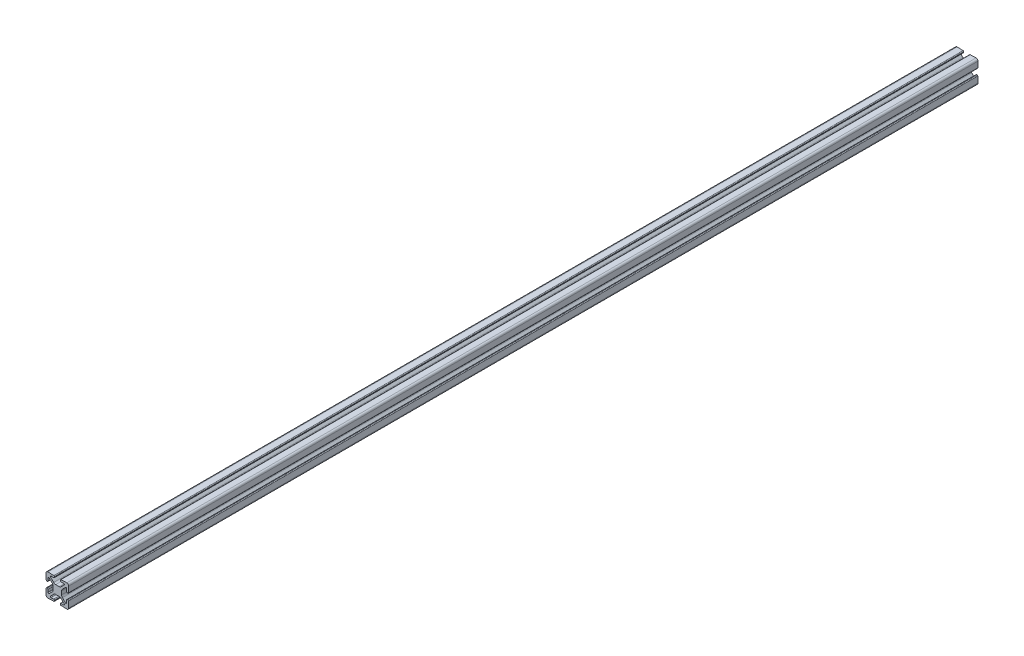
SolidWorks part; units mm, degrees
ref_plane "Front Plane" through (0, 0, 0) normal (0, 0, 1) x (1, 0, 0)
ref_plane "Top Plane" through (0, 0, 0) normal (0, 1, 0) x (1, 0, 0)
ref_plane "Right Plane" through (0, 0, 0) normal (1, 0, 0) x (0, 0, -1)
sketch "Sketch1" plane through (0, 0, 0) normal (0, 0, 1) x (1, 0, 0)
  line L0 (0, 0) -> (0, 12.7) construction
  line L1 (0, 0) -> (12.7, 0) construction
  line L2 (0, 0) -> (-12.7, 12.7) construction
  line L3 (-10.5971, 12.6988) -> (-3.9739, 12.4675)
  line L4 (-12.7, 12.7) -> (0, 12.7) construction
  line L6 (-4.0475, 10.3606) -> (-7.0332, 10.4648)
  line L10 (0, 4.7625) -> (-1.8848, 4.7625)
  line L11 (-4.1299, 5.6924) -> (-7.5996, 9.1622)
  line L24 (0, 0) -> (-12.7, 0) construction
  line L25 (-12.7, 0) -> (0, 0) construction
  line L26 (0, 0) -> (0, -12.7) construction
  line L27 (-12.7, -12.7) -> (-12.7, 12.7) construction
  line L28 (0, 12.7) -> (12.7, 12.7) construction
  line L29 (-3.239, 11.6793) -> (-3.2594, 11.0955)
  line L30 (-12.7, -12.7) -> (12.7, -12.7) construction
  arc A0 (-12.1048, 12.1048) -> (-10.5971, 12.6988) centre (-10.668, 10.668) cw
  arc A6 (-1.8848, 4.7625) -> (-4.1299, 5.6924) centre (-1.8848, 7.9375) cw
  circle A16 centre (0, 0) radius 2.54
  arc A18 (-7.5996, 9.1622) -> (-7.0332, 10.4648) centre (-7.0599, 9.702) cw
  circle A19 centre (-2.3794, 2.3794) radius 0.635 construction
  arc A20 (-4.0475, 10.3606) -> (-3.2594, 11.0955) centre (-4.0209, 11.1221) ccw
  arc A21 (-3.9739, 12.4675) -> (-3.239, 11.6793) centre (-4.0005, 11.7059) cw
  point P15 (0, 0)
  point P42 (-3.1999, 4.7625)
  point P80 (-12.7, 0)
  point P85 (0, -12.7)
  point P88 (0, -12.7)
  dimension "D11" = 2.032
  dimension "D15" = 3.175
  dimension "Center Hole Diameter" = 5.08
  dimension "D6" = 1.27
  dimension "D4" = 0.7633
  dimension "D8" = 0.762
  dimension "D12" = 0.762
  dimension "D1" = 45
  dimension "D2" = 2
  dimension "Rail Width" = 25.4
  dimension "D10" = 2.2098
  dimension "T-Slot Depth" = 7.9375
  dimension "D9" = 2.1082
  dimension "Rail Height" = 25.4
  dimension "D23" = 9.525
  dimension "D5" = 15.6464
  dimension "D3" = 4
  dimension "D7" = 5.7028
  dimension "T-Slot Width" = 6.477
sketch "Sketch2" plane through (0, 0, 0) normal (1, 0, 0) x (0, 0, -1)
  line L0 (-457.2, 0) -> (457.2, 0)
  line L2 (0, 0) -> (0, 12.7) construction
  line L3 (0, 0) -> (0, 12.7) construction
  point P0 (-419.1, 0)
  point P3 (0, 0)
  point P7 (419.1, 0)
  dimension "D1" = 38.1
  dimension "Length" = 914.4
sketch "Sketch3" plane through (0, 0, 0) normal (0, 0, 1) x (1, 0, 0)
  line L2 (0, 4.7625) -> (-1.8848, 4.7625) construction
  line L5 (-4.1299, 5.6924) -> (-7.5996, 9.1622) construction
  line L6 (-4.0475, 10.3606) -> (-7.0332, 10.4648) construction
  line L7 (-3.239, 11.6793) -> (-3.2594, 11.0955) construction
  line L67 (-10.5971, 12.6988) -> (-3.9739, 12.4675) construction
  line L68 (0, 4.7625) -> (-1.8848, 4.7625)
  line L69 (-4.1299, 5.6924) -> (-7.5996, 9.1622)
  line L70 (-4.0475, 10.3606) -> (-7.0332, 10.4648)
  line L71 (-3.239, 11.6793) -> (-3.2594, 11.0955)
  line L72 (-10.5971, 12.6988) -> (-3.9739, 12.4675)
  line L73 (0, 0) -> (-12.7, 12.7) construction
  line L74 (0, 0) -> (-12.7, 12.7) construction
  line L75 (-12.6988, 10.5971) -> (-12.4675, 3.9739)
  line L76 (-11.6793, 3.239) -> (-11.0955, 3.2594)
  line L77 (-10.3606, 4.0475) -> (-10.4648, 7.0332)
  line L78 (-5.6924, 4.1299) -> (-9.1622, 7.5996)
  line L79 (-4.7625, 0) -> (-4.7625, 1.8848)
  line L80 (-4.7625, 0) -> (-2.54, 0)
  line L82 (0, 4.7625) -> (0, 2.54)
  arc A3 (-4.1299, 5.6924) -> (-1.8848, 4.7625) centre (-1.8848, 7.9375) ccw construction
  circle A10 centre (0, 0) radius 2.54
  arc A56 (0, 2.54) -> (-2.54, 0) centre (0, 0) ccw
  arc A57 (-7.0332, 10.4648) -> (-7.5996, 9.1622) centre (-7.0599, 9.702) ccw construction
  arc A58 (-4.0475, 10.3606) -> (-3.2594, 11.0955) centre (-4.0209, 11.1221) ccw construction
  arc A59 (-3.239, 11.6793) -> (-3.9739, 12.4675) centre (-4.0005, 11.7059) ccw construction
  arc A60 (-10.5971, 12.6988) -> (-12.1048, 12.1048) centre (-10.668, 10.668) ccw construction
  arc A61 (-4.1299, 5.6924) -> (-1.8848, 4.7625) centre (-1.8848, 7.9375) ccw
  arc A62 (-7.0332, 10.4648) -> (-7.5996, 9.1622) centre (-7.0599, 9.702) ccw
  arc A63 (-4.0475, 10.3606) -> (-3.2594, 11.0955) centre (-4.0209, 11.1221) ccw
  arc A64 (-3.239, 11.6793) -> (-3.9739, 12.4675) centre (-4.0005, 11.7059) ccw
  arc A65 (-10.5971, 12.6988) -> (-12.6988, 10.5971) centre (-10.668, 10.668) ccw
  arc A67 (-11.6793, 3.239) -> (-12.4675, 3.9739) centre (-11.7059, 4.0005) cw
  arc A68 (-10.3606, 4.0475) -> (-11.0955, 3.2594) centre (-11.1221, 4.0209) cw
  arc A69 (-10.4648, 7.0332) -> (-9.1622, 7.5996) centre (-9.702, 7.0599) cw
  arc A70 (-5.6924, 4.1299) -> (-4.7625, 1.8848) centre (-7.9375, 1.8848) cw
  dimension "D1" = 0
extrude "Boss-Extrude1" add sketch "Sketch3" along normal mid plane 914.4
pattern_circular "CirPattern1" count 4 over 360 about axis through (0, 0, 0) along (0, 0, 1) of "Boss-Extrude1"
ref_plane "Contact Plane 1" through (0, 12.7, 0) normal (0, 1, 0) x (1, 0, 0)
ref_plane "Contact Plane 2" through (12.7, 0, 0) normal (1, 0, 0) x (0, 0, -1)
ref_plane "Contact Plane 3" through (0, -12.7, 0) normal (0, -1, 0) x (-1, 0, 0)
ref_plane "Contact Plane 4" through (-12.7, 0, 0) normal (-1, 0, 0) x (0, 0, 1)
sketch "Sketch4" plane through (0, 0, 457.2) normal (0, 0, 1) x (1, 0, 0)
  line L36 (1.8848, 4.7625) -> (-1.8848, 4.7625)
  line L37 (-4.1299, 5.6924) -> (-7.5996, 9.1622)
  line L38 (-7.0332, 10.4648) -> (-4.0475, 10.3606)
  line L39 (-3.2594, 11.0955) -> (-3.239, 11.6793)
  line L40 (-3.9739, 12.4675) -> (-10.5971, 12.6988)
  line L41 (-12.6988, 10.5971) -> (-12.4675, 3.9739)
  line L42 (-11.6793, 3.239) -> (-11.0955, 3.2594)
  line L43 (-10.3606, 4.0475) -> (-10.4648, 7.0332)
  line L44 (-9.1622, 7.5996) -> (-5.6924, 4.1299)
  line L45 (-4.7625, 1.8848) -> (-4.7625, -1.8848)
  line L46 (-5.6924, -4.1299) -> (-9.1622, -7.5996)
  line L47 (-10.4648, -7.0332) -> (-10.3606, -4.0475)
  line L48 (-11.0955, -3.2594) -> (-11.6793, -3.239)
  line L49 (-12.4675, -3.9739) -> (-12.6988, -10.5971)
  line L50 (-10.5971, -12.6988) -> (-3.9739, -12.4675)
  line L51 (-3.239, -11.6793) -> (-3.2594, -11.0955)
  line L52 (-4.0475, -10.3606) -> (-7.0332, -10.4648)
  line L53 (-7.5996, -9.1622) -> (-4.1299, -5.6924)
  line L54 (-1.8848, -4.7625) -> (1.8848, -4.7625)
  line L55 (4.1299, -5.6924) -> (7.5996, -9.1622)
  line L56 (7.0332, -10.4648) -> (4.0475, -10.3606)
  line L57 (3.2594, -11.0955) -> (3.239, -11.6793)
  line L58 (3.9739, -12.4675) -> (10.5971, -12.6988)
  line L59 (12.6988, -10.5971) -> (12.4675, -3.9739)
  line L60 (11.6793, -3.239) -> (11.0955, -3.2594)
  line L61 (10.3606, -4.0475) -> (10.4648, -7.0332)
  line L62 (9.1622, -7.5996) -> (5.6924, -4.1299)
  line L63 (4.7625, -1.8848) -> (4.7625, 1.8848)
  line L64 (5.6924, 4.1299) -> (9.1622, 7.5996)
  line L65 (10.4648, 7.0332) -> (10.3606, 4.0475)
  line L66 (11.0955, 3.2594) -> (11.6793, 3.239)
  line L67 (12.4675, 3.9739) -> (12.6988, 10.5971)
  line L68 (10.5971, 12.6988) -> (3.9739, 12.4675)
  line L69 (3.239, 11.6793) -> (3.2594, 11.0955)
  line L70 (4.0475, 10.3606) -> (7.0332, 10.4648)
  line L71 (7.5996, 9.1622) -> (4.1299, 5.6924)
  line L72 (1.8848, 4.7625) -> (-1.8848, 4.7625)
  line L73 (-4.1299, 5.6924) -> (-7.5996, 9.1622)
  line L74 (-7.0332, 10.4648) -> (-4.0475, 10.3606)
  line L75 (-3.2594, 11.0955) -> (-3.239, 11.6793)
  line L76 (-3.9739, 12.4675) -> (-10.5971, 12.6988)
  line L77 (-12.6988, 10.5971) -> (-12.4675, 3.9739)
  line L78 (-11.6793, 3.239) -> (-11.0955, 3.2594)
  line L79 (-10.3606, 4.0475) -> (-10.4648, 7.0332)
  line L80 (-9.1622, 7.5996) -> (-5.6924, 4.1299)
  line L81 (-4.7625, 1.8848) -> (-4.7625, -1.8848)
  line L82 (-5.6924, -4.1299) -> (-9.1622, -7.5996)
  line L83 (-10.4648, -7.0332) -> (-10.3606, -4.0475)
  line L84 (-11.0955, -3.2594) -> (-11.6793, -3.239)
  line L85 (-12.4675, -3.9739) -> (-12.6988, -10.5971)
  line L86 (-10.5971, -12.6988) -> (-3.9739, -12.4675)
  line L87 (-3.239, -11.6793) -> (-3.2594, -11.0955)
  line L88 (-4.0475, -10.3606) -> (-7.0332, -10.4648)
  line L89 (-7.5996, -9.1622) -> (-4.1299, -5.6924)
  line L90 (-1.8848, -4.7625) -> (1.8848, -4.7625)
  line L91 (4.1299, -5.6924) -> (7.5996, -9.1622)
  line L92 (7.0332, -10.4648) -> (4.0475, -10.3606)
  line L93 (3.2594, -11.0955) -> (3.239, -11.6793)
  line L94 (3.9739, -12.4675) -> (10.5971, -12.6988)
  line L95 (12.6988, -10.5971) -> (12.4675, -3.9739)
  line L96 (11.6793, -3.239) -> (11.0955, -3.2594)
  line L97 (10.3606, -4.0475) -> (10.4648, -7.0332)
  line L98 (9.1622, -7.5996) -> (5.6924, -4.1299)
  line L99 (4.7625, -1.8848) -> (4.7625, 1.8848)
  line L100 (5.6924, 4.1299) -> (9.1622, 7.5996)
  line L101 (10.4648, 7.0332) -> (10.3606, 4.0475)
  line L102 (11.0955, 3.2594) -> (11.6793, 3.239)
  line L103 (12.4675, 3.9739) -> (12.6988, 10.5971)
  line L104 (10.5971, 12.6988) -> (3.9739, 12.4675)
  line L105 (3.239, 11.6793) -> (3.2594, 11.0955)
  line L106 (4.0475, 10.3606) -> (7.0332, 10.4648)
  line L107 (7.5996, 9.1622) -> (4.1299, 5.6924)
  arc A36 (1.8848, 4.7625) -> (4.1299, 5.6924) centre (1.8848, 7.9375) ccw
  arc A37 (-4.1299, 5.6924) -> (-1.8848, 4.7625) centre (-1.8848, 7.9375) ccw
  arc A38 (-7.0332, 10.4648) -> (-7.5996, 9.1622) centre (-7.0599, 9.702) ccw
  arc A39 (-4.0475, 10.3606) -> (-3.2594, 11.0955) centre (-4.0209, 11.1221) ccw
  arc A40 (-3.239, 11.6793) -> (-3.9739, 12.4675) centre (-4.0005, 11.7059) ccw
  arc A41 (-10.5971, 12.6988) -> (-12.6988, 10.5971) centre (-10.668, 10.668) ccw
  arc A42 (-12.4675, 3.9739) -> (-11.6793, 3.239) centre (-11.7059, 4.0005) ccw
  arc A43 (-11.0955, 3.2594) -> (-10.3606, 4.0475) centre (-11.1221, 4.0209) ccw
  arc A44 (-9.1622, 7.5996) -> (-10.4648, 7.0332) centre (-9.702, 7.0599) ccw
  arc A45 (-4.7625, 1.8848) -> (-5.6924, 4.1299) centre (-7.9375, 1.8848) ccw
  arc A46 (-5.6924, -4.1299) -> (-4.7625, -1.8848) centre (-7.9375, -1.8848) ccw
  arc A47 (-10.4648, -7.0332) -> (-9.1622, -7.5996) centre (-9.702, -7.0599) ccw
  arc A48 (-10.3606, -4.0475) -> (-11.0955, -3.2594) centre (-11.1221, -4.0209) ccw
  arc A49 (-11.6793, -3.239) -> (-12.4675, -3.9739) centre (-11.7059, -4.0005) ccw
  arc A50 (-12.6988, -10.5971) -> (-10.5971, -12.6988) centre (-10.668, -10.668) ccw
  arc A51 (-3.9739, -12.4675) -> (-3.239, -11.6793) centre (-4.0005, -11.7059) ccw
  arc A52 (-3.2594, -11.0955) -> (-4.0475, -10.3606) centre (-4.0209, -11.1221) ccw
  arc A53 (-7.5996, -9.1622) -> (-7.0332, -10.4648) centre (-7.0599, -9.702) ccw
  arc A54 (-1.8848, -4.7625) -> (-4.1299, -5.6924) centre (-1.8848, -7.9375) ccw
  arc A55 (4.1299, -5.6924) -> (1.8848, -4.7625) centre (1.8848, -7.9375) ccw
  arc A56 (7.0332, -10.4648) -> (7.5996, -9.1622) centre (7.0599, -9.702) ccw
  arc A57 (4.0475, -10.3606) -> (3.2594, -11.0955) centre (4.0209, -11.1221) ccw
  arc A58 (3.239, -11.6793) -> (3.9739, -12.4675) centre (4.0005, -11.7059) ccw
  arc A59 (10.5971, -12.6988) -> (12.6988, -10.5971) centre (10.668, -10.668) ccw
  arc A60 (12.4675, -3.9739) -> (11.6793, -3.239) centre (11.7059, -4.0005) ccw
  arc A61 (11.0955, -3.2594) -> (10.3606, -4.0475) centre (11.1221, -4.0209) ccw
  arc A62 (9.1622, -7.5996) -> (10.4648, -7.0332) centre (9.702, -7.0599) ccw
  arc A63 (4.7625, -1.8848) -> (5.6924, -4.1299) centre (7.9375, -1.8848) ccw
  arc A64 (5.6924, 4.1299) -> (4.7625, 1.8848) centre (7.9375, 1.8848) ccw
  arc A65 (10.4648, 7.0332) -> (9.1622, 7.5996) centre (9.702, 7.0599) ccw
  arc A66 (10.3606, 4.0475) -> (11.0955, 3.2594) centre (11.1221, 4.0209) ccw
  arc A67 (11.6793, 3.239) -> (12.4675, 3.9739) centre (11.7059, 4.0005) ccw
  arc A68 (12.6988, 10.5971) -> (10.5971, 12.6988) centre (10.668, 10.668) ccw
  arc A69 (3.9739, 12.4675) -> (3.239, 11.6793) centre (4.0005, 11.7059) ccw
  arc A70 (3.2594, 11.0955) -> (4.0475, 10.3606) centre (4.0209, 11.1221) ccw
  arc A71 (7.5996, 9.1622) -> (7.0332, 10.4648) centre (7.0599, 9.702) ccw
  arc A72 (1.8848, 4.7625) -> (4.1299, 5.6924) centre (1.8848, 7.9375) ccw
  arc A73 (-4.1299, 5.6924) -> (-1.8848, 4.7625) centre (-1.8848, 7.9375) ccw
  arc A74 (-7.0332, 10.4648) -> (-7.5996, 9.1622) centre (-7.0599, 9.702) ccw
  arc A75 (-4.0475, 10.3606) -> (-3.2594, 11.0955) centre (-4.0209, 11.1221) ccw
  arc A76 (-3.239, 11.6793) -> (-3.9739, 12.4675) centre (-4.0005, 11.7059) ccw
  arc A77 (-10.5971, 12.6988) -> (-12.6988, 10.5971) centre (-10.668, 10.668) ccw
  arc A78 (-12.4675, 3.9739) -> (-11.6793, 3.239) centre (-11.7059, 4.0005) ccw
  arc A79 (-11.0955, 3.2594) -> (-10.3606, 4.0475) centre (-11.1221, 4.0209) ccw
  arc A80 (-9.1622, 7.5996) -> (-10.4648, 7.0332) centre (-9.702, 7.0599) ccw
  arc A81 (-4.7625, 1.8848) -> (-5.6924, 4.1299) centre (-7.9375, 1.8848) ccw
  arc A82 (-5.6924, -4.1299) -> (-4.7625, -1.8848) centre (-7.9375, -1.8848) ccw
  arc A83 (-10.4648, -7.0332) -> (-9.1622, -7.5996) centre (-9.702, -7.0599) ccw
  arc A84 (-10.3606, -4.0475) -> (-11.0955, -3.2594) centre (-11.1221, -4.0209) ccw
  arc A85 (-11.6793, -3.239) -> (-12.4675, -3.9739) centre (-11.7059, -4.0005) ccw
  arc A86 (-12.6988, -10.5971) -> (-10.5971, -12.6988) centre (-10.668, -10.668) ccw
  arc A87 (-3.9739, -12.4675) -> (-3.239, -11.6793) centre (-4.0005, -11.7059) ccw
  arc A88 (-3.2594, -11.0955) -> (-4.0475, -10.3606) centre (-4.0209, -11.1221) ccw
  arc A89 (-7.5996, -9.1622) -> (-7.0332, -10.4648) centre (-7.0599, -9.702) ccw
  arc A90 (-1.8848, -4.7625) -> (-4.1299, -5.6924) centre (-1.8848, -7.9375) ccw
  arc A91 (4.1299, -5.6924) -> (1.8848, -4.7625) centre (1.8848, -7.9375) ccw
  arc A92 (7.0332, -10.4648) -> (7.5996, -9.1622) centre (7.0599, -9.702) ccw
  arc A93 (4.0475, -10.3606) -> (3.2594, -11.0955) centre (4.0209, -11.1221) ccw
  arc A94 (3.239, -11.6793) -> (3.9739, -12.4675) centre (4.0005, -11.7059) ccw
  arc A95 (10.5971, -12.6988) -> (12.6988, -10.5971) centre (10.668, -10.668) ccw
  arc A96 (12.4675, -3.9739) -> (11.6793, -3.239) centre (11.7059, -4.0005) ccw
  arc A97 (11.0955, -3.2594) -> (10.3606, -4.0475) centre (11.1221, -4.0209) ccw
  arc A98 (9.1622, -7.5996) -> (10.4648, -7.0332) centre (9.702, -7.0599) ccw
  arc A99 (4.7625, -1.8848) -> (5.6924, -4.1299) centre (7.9375, -1.8848) ccw
  arc A100 (5.6924, 4.1299) -> (4.7625, 1.8848) centre (7.9375, 1.8848) ccw
  arc A101 (10.4648, 7.0332) -> (9.1622, 7.5996) centre (9.702, 7.0599) ccw
  arc A102 (10.3606, 4.0475) -> (11.0955, 3.2594) centre (11.1221, 4.0209) ccw
  arc A103 (11.6793, 3.239) -> (12.4675, 3.9739) centre (11.7059, 4.0005) ccw
  arc A104 (12.6988, 10.5971) -> (10.5971, 12.6988) centre (10.668, 10.668) ccw
  arc A105 (3.9739, 12.4675) -> (3.239, 11.6793) centre (4.0005, 11.7059) ccw
  arc A106 (3.2594, 11.0955) -> (4.0475, 10.3606) centre (4.0209, 11.1221) ccw
  arc A107 (7.5996, 9.1622) -> (7.0332, 10.4648) centre (7.0599, 9.702) ccw
  dimension "D1" = 0
extrude "Boss-Extrude2" add sketch "Sketch4" along normal blind 101.6
equation "\"D1@Sketch2\"=\"Rail Width@Sketch1\"*1.5"
equation "\"D1@Boss-Extrude1\"=\"Length@Sketch2\""
